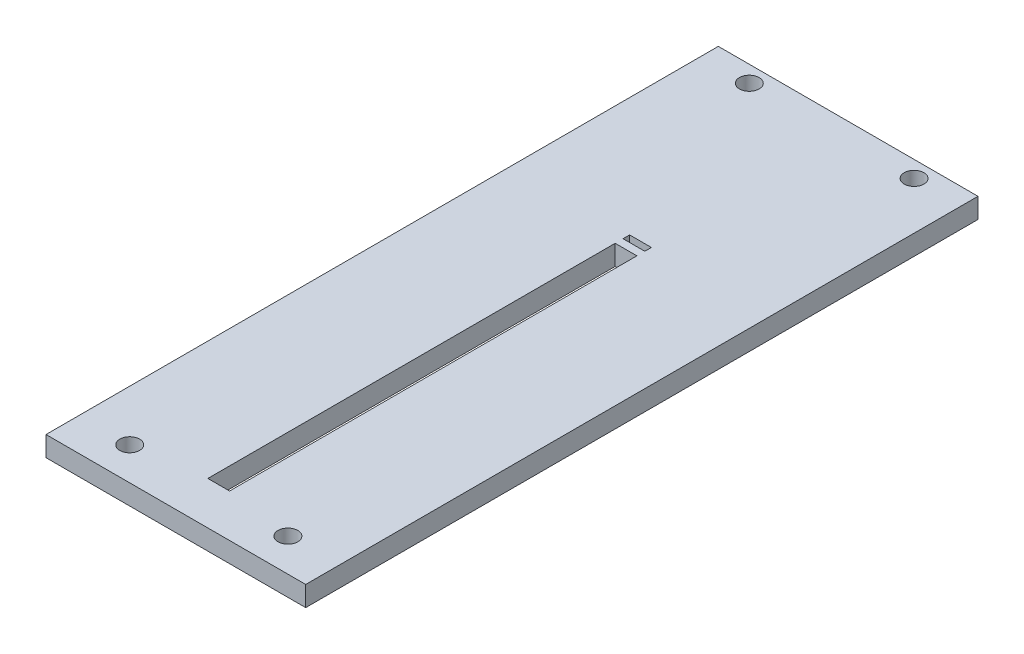
SolidWorks part; units mm, degrees
ref_plane "Front Plane" through (0, 0, 0) normal (0, 0, 1) x (1, 0, 0)
ref_plane "Top Plane" through (0, 0, 0) normal (0, 1, 0) x (1, 0, 0)
ref_plane "Right Plane" through (0, 0, 0) normal (1, 0, 0) x (0, 0, -1)
sketch "Sketch1" plane through (0, 0, 0) normal (0, 1, 0) x (1, 0, 0)
  line L1 (-19.7, 0) -> (19.7, 0)
  line L2 (-19.7, 0) -> (-19.7, 102)
  line L3 (-19.7, 102) -> (19.7, 102)
  line L4 (19.7, 0) -> (19.7, 102)
  point P5 (0, 0)
  dimension "D1" = 39.4
  dimension "D2" = 102
extrude "Boss-Extrude1" add sketch "Sketch1" along normal blind 3.05
sketch "Sketch4" plane through (0, 3.05, 0) normal (0, 1, 0) x (1, 0, 0)
  line L0 (-19.7, 102) -> (19.7, 102) construction
  line L2 (-19.7, 0) -> (19.7, 0) construction
  line L3 (1.65, 70.5) -> (-1.65, 70.5)
  line L4 (-1.65, 70.5) -> (-1.65, 69.5)
  line L5 (-1.65, 69.5) -> (1.65, 69.5)
  line L6 (1.65, 69.5) -> (1.65, 70.5)
  line L7 (0, 0) -> (0, 102) construction
  line L9 (1.65, 68.3) -> (-1.65, 68.3)
  line L10 (-1.65, 68.3) -> (-1.65, 6.5)
  line L11 (-1.65, 6.5) -> (1.65, 6.5)
  line L12 (1.65, 6.5) -> (1.65, 68.3)
  point P6 (0, 6.5)
  point P10 (0, 70.5)
  point P22 (0, 68.3)
  dimension "D1" = 61.8
  dimension "D2" = 1
  dimension "D3" = 1.2
  dimension "D4" = 3.3
  dimension "D7" = 6.5
extrude "Cut-Extrude1" cut sketch "Sketch4" against normal through all contours L5 L7 L3 L4 | L11 L7 L9 L10 | L7 L11 L12 L9 | L7 L5 L6 L3
sketch "Sketch7" plane through (0, 3.05, 0) normal (0, 1, 0) x (1, 0, 0)
  line L0 (0, 0) -> (-12, 0)
  line L1 (-19.7, 0) -> (19.7, 0) construction
  line L2 (-12, 0) -> (-12, 5)
  line L4 (0, 0) -> (0, 70) construction
  circle A0 centre (-12, 5) radius 1.5
  circle A2 centre (12, 5) radius 1.5
  dimension "D3" = 3
  dimension "D1" = 12
  dimension "D2" = 5
extrude "Cut-Extrude4" cut sketch "Sketch7" against normal through all
hole_wizard "Ø3.0mm Dowel Hole1" positions "Sketch8" profile "Sketch9" hole size "Ø3.0" standard "ANSI Metric" end condition through all
sketch "Sketch8" plane through (0, 3.05, 0) normal (0, 1, 0) x (1, 0, 0)
  line L0 (0, 87.5332) -> (0, 2.5332) construction
  line L3 (-19.7, 102) -> (19.7, 102) construction
  point P0 (-12.5, 99.5)
  point P2 (12.5, 99.5)
  dimension "D1" = 12.5
  dimension "D2" = 2.5
sketch "Sketch9" plane through (-12.5, 3.05, -99.5) normal (1, 0, 0) x (0, 0, 1)
  line L0 (0, 0) -> (0, 3.05)
  line L1 (0, 3.05) -> (1.5, 3.05)
  line L2 (1.5, 3.05) -> (1.5, 0)
  line L5 (1.5, 0) -> (0, 0)
  line L11 (0, -6.35) -> (0, 107.95) construction
  dimension "Thru Hole Dia." = 3
  dimension "Thru Hole Depth" = 3.05
